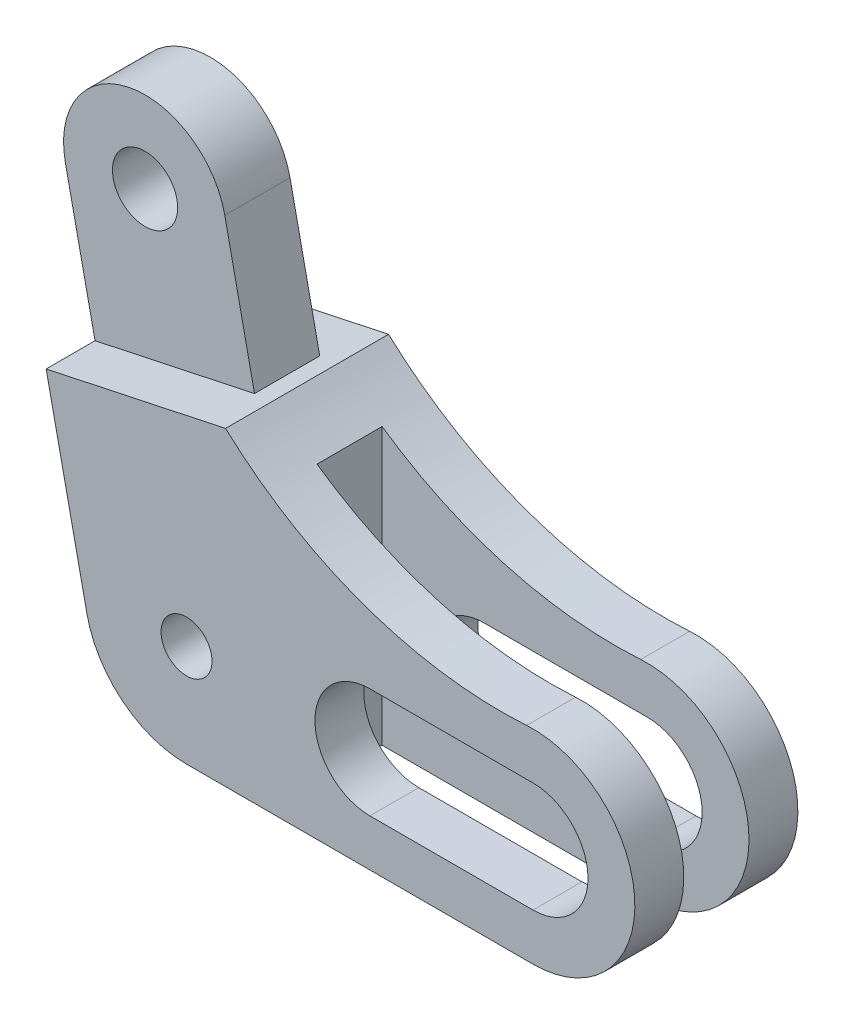
SolidWorks part; units mm, degrees
ref_plane "Front Plane" through (0, 0, 0) normal (0, 0, 1) x (1, 0, 0)
ref_plane "Top Plane" through (0, 0, 0) normal (0, 1, 0) x (1, 0, 0)
ref_plane "Right Plane" through (0, 0, 0) normal (1, 0, 0) x (0, 0, -1)
sketch "Sketch2" plane through (0, 0, 0) normal (0, 0, 1) x (1, 0, 0)
  line L0 (-37.3095, 0) -> (85, 0) construction
  line L1 (0, 36.0339) -> (0, -42.6242) construction
  line L2 (0, -25) -> (85, -25)
  line L3 (9.5667, 51.1124) -> (-34.447, 41.7421)
  line L4 (-34.447, 41.7421) -> (-24.452, -5.2057)
  line L5 (-12.4402, 46.4273) -> (0, 0) construction
  line L6 (85, 0) -> (45, 0) construction
  line L7 (85, -13.5) -> (45, -13.5)
  line L8 (85, 13.5) -> (45, 13.5)
  arc A0 (85, -25) -> (83.4432, 24.9515) centre (85, 0) ccw
  arc A1 (83.4432, 24.9515) -> (9.5667, 51.1124) centre (77.2159, 124.7574) cw
  arc A2 (-24.452, -5.2057) -> (0, -25) centre (0, 0) ccw
  arc A3 (85, -13.5) -> (85, 13.5) centre (85, 0) ccw
  arc A4 (45, 13.5) -> (45, -13.5) centre (45, 0) ccw
  circle A5 centre (0, 0) radius 6.25
  point P7 (65, 0)
  point P16 (0, 0)
  point P22 (0, 0)
  point P23 (75.8375, 0)
  dimension "D1" = 25
  dimension "D2" = 13.5
  dimension "D6" = 100
  dimension "D9" = 12.5
  dimension "D3" = 40
  dimension "D4" = 45
  dimension "D5" = 48
  dimension "D7" = 45
  dimension "D8" = 15
extrude "Boss-Extrude1" add sketch "Sketch2" along normal mid plane 40
sketch "Sketch4" plane through (0, 0, 0) normal (0, 1, 0) x (1, 0, 0)
  line L0 (110, -20) -> (110, 20) construction
  line L1 (0, 0) -> (110, 0) construction
  line L2 (110, 8) -> (20, 8)
  line L3 (110, 8) -> (110, -8)
  line L4 (110, -8) -> (20, -8)
  line L5 (20, 8) -> (20, -8)
  dimension "D1" = 90
  dimension "D2" = 16
extrude "Cut-Extrude1" cut sketch "Sketch4" against normal through all both and the other way through all
sketch "Sketch5" plane through (0, 0, 0) normal (0, 0, 1) x (1, 0, 0)
  line L0 (-34.447, 41.7421) -> (-41.7349, 75.975)
  line L1 (-2.6117, 84.3041) -> (4.6763, 50.0713)
  line L2 (9.5667, 51.1124) -> (-34.447, 41.7421) construction
  line L3 (4.6763, 50.0713) -> (-34.447, 41.7421)
  arc A0 (-41.7349, 75.975) -> (-2.6117, 84.3041) centre (-22.1733, 80.1395) cw
  circle A1 centre (-22.1733, 80.1395) radius 8
  dimension "D2" = 20
  dimension "D3" = 16
  dimension "D1" = 35
extrude "Boss-Extrude2" add sketch "Sketch5" along normal mid plane 16
